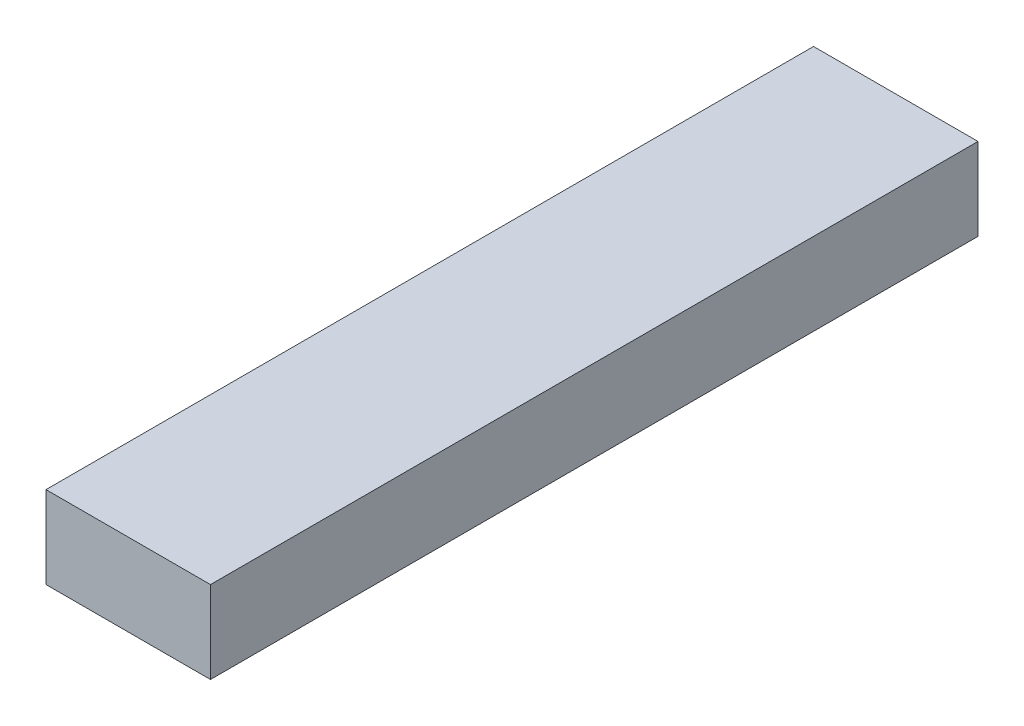
SolidWorks part; units mm, degrees
material "Alloy Steel"
ref_plane "Front Plane" through (0, 0, 0) normal (0, 0, 1) x (1, 0, 0)
ref_plane "Top Plane" through (0, 0, 0) normal (0, 1, 0) x (1, 0, 0)
ref_plane "Right Plane" through (0, 0, 0) normal (1, 0, 0) x (0, 0, -1)
sketch "Sketch2" plane through (0, 0, 0) normal (0, 0, 1) x (1, 0, 0)
  line L1 (0, 0) -> (9.525, 0)
  line L2 (0, 0) -> (0, 4.7625)
  line L3 (0, 4.7625) -> (9.525, 4.7625)
  line L4 (9.525, 0) -> (9.525, 4.7625)
  dimension "D1" = 4.7625
  dimension "D2" = 9.525
extrude "Boss-Extrude1" add sketch "Sketch2" against normal blind 44.45
